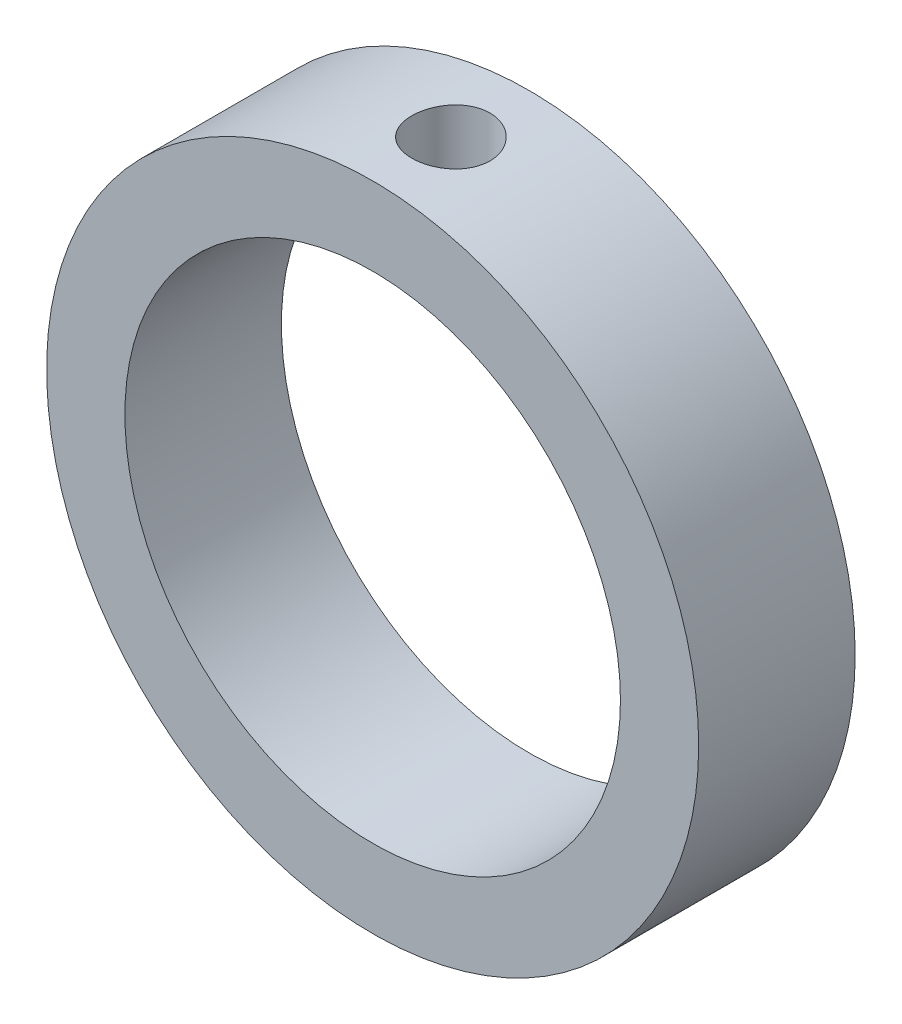
SolidWorks part; units mm, degrees
material "Aluminum Bronze"
ref_plane "Front Plane" through (0, 0, 0) normal (0, 0, 1) x (1, 0, 0)
ref_plane "Top Plane" through (0, 0, 0) normal (0, 1, 0) x (1, 0, 0)
ref_plane "Right Plane" through (0, 0, 0) normal (1, 0, 0) x (0, 0, -1)
sketch "Sketch1" plane through (0, 0, 0) normal (0, 0, 1) x (1, 0, 0)
  circle A0 centre (0, 0) radius 9.5
  circle A1 centre (0, 0) radius 12.5
  dimension "D1" = 25
  dimension "D2" = 19
extrude "Boss-Extrude1" add sketch "Sketch1" along normal mid plane 6
sketch "Sketch2" plane through (0, 0, 0) normal (0, 1, 0) x (1, 0, 0)
  circle A0 centre (0, 0) radius 1.5
  dimension "D1" = 3
extrude "Cut-Extrude1" cut sketch "Sketch2" along normal up to next
cosmetic thread "Cosmetic Thread1" parameters "D2"=4
